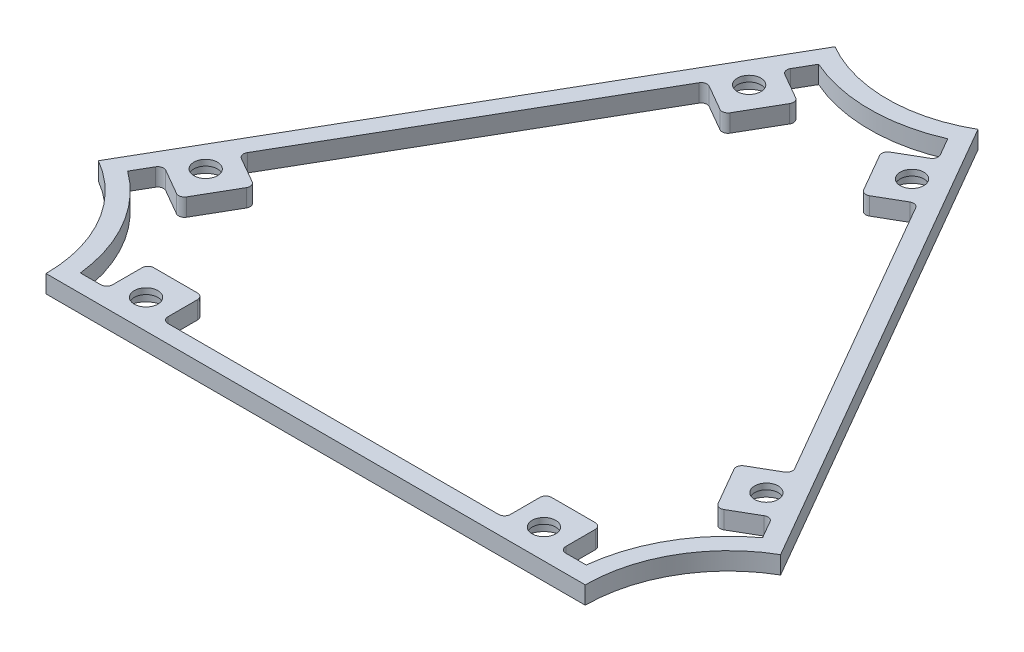
SolidWorks part; units mm, degrees
ref_plane "Front Plane" through (0, 0, 0) normal (0, 0, 1) x (1, 0, 0)
ref_plane "Top Plane" through (0, 0, 0) normal (0, 1, 0) x (1, 0, 0)
ref_plane "Right Plane" through (0, 0, 0) normal (1, 0, 0) x (0, 0, -1)
sketch "Sketch2" plane through (0, 0, 0) normal (0, 1, 0) x (1, 0, 0)
  line L0 (-46.9523, -6.4506) -> (-41.8901, -9.3732) construction
  line L1 (-41.3901, -10.8166) -> (-45.0901, -17.2252) construction
  line L2 (-46.5901, -17.5139) -> (-51.6523, -14.5912) construction
  line L3 (-51.6523, -14.5912) -> (-55.3023, -20.9132) construction
  line L4 (11.8276, 40.3871) -> (11.3276, 41.2532)
  line L5 (-57.9003, -19.4132) -> (-45.9003, 1.3714) construction
  line L6 (29.0625, -30.4366) -> (38.4625, -30.4366)
  line L7 (-43.3023, -0.1286) -> (-46.9523, -6.4506) construction
  line L8 (-38.4625, -37.4366) -> (-38.4625, -31.5913) construction
  line L9 (-37.4625, -30.4366) -> (-30.0625, -30.4366) construction
  line L10 (-29.0625, -31.5913) -> (-29.0625, -37.4366) construction
  line L11 (-29.0625, -37.4366) -> (-21.7625, -37.4366) construction
  line L12 (-40.8901, -9.9506) -> (-45.5901, -18.0912)
  line L13 (-21.7625, -40.4366) -> (-45.7625, -40.4366) construction
  line L14 (49.0148, -28.2987) -> (46.4168, -26.7987) construction
  line L15 (-45.7625, -37.4366) -> (-38.4625, -37.4366) construction
  line L16 (29.0625, -37.4366) -> (29.0625, -31.5913) construction
  line L17 (30.0625, -30.4366) -> (37.4625, -30.4366) construction
  line L18 (38.4625, -31.5913) -> (38.4625, -37.4366) construction
  line L19 (38.4625, -37.4366) -> (45.7625, -37.4366) construction
  line L20 (0, 53.5974) -> (0, 56.5974) construction
  line L21 (45.7625, -40.4366) -> (21.7625, -40.4366) construction
  line L22 (-46.4168, -26.7987) -> (-49.0148, -28.2987) construction
  line L23 (21.7625, -37.4366) -> (29.0625, -37.4366) construction
  line L24 (51.6523, -14.5912) -> (46.5901, -17.5139) construction
  line L25 (45.0901, -17.2252) -> (41.3901, -10.8166) construction
  line L26 (41.8901, -9.3732) -> (46.9523, -6.4506) construction
  line L27 (46.9523, -6.4506) -> (43.3023, -0.1286) construction
  line L29 (45.9003, 1.3714) -> (57.9003, -19.4132) construction
  line L31 (55.3023, -20.9132) -> (51.6523, -14.5912) construction
  line L32 (11.3276, 41.2532) -> (7.6276, 47.6618) construction
  line L33 (8.1276, 49.1051) -> (13.1898, 52.0278) construction
  line L34 (13.1898, 52.0278) -> (9.5398, 58.3498) construction
  line L36 (12.1378, 59.8498) -> (24.1378, 39.0652) construction
  line L38 (21.5398, 37.5652) -> (17.8898, 43.8871) construction
  line L39 (17.8898, 43.8871) -> (12.8276, 40.9645) construction
  line L40 (-13.1898, 52.0278) -> (-8.1276, 49.1051) construction
  line L41 (-7.6276, 47.6618) -> (-11.3276, 41.2532) construction
  line L42 (-12.8276, 40.9645) -> (-17.8898, 43.8871) construction
  line L43 (-17.8898, 43.8871) -> (-21.5398, 37.5652) construction
  line L45 (-24.1378, 39.0652) -> (-12.1378, 59.8498) construction
  line L47 (-9.5398, 58.3498) -> (-13.1898, 52.0278) construction
  line L48 (-46.9523, -6.4506) -> (-40.8901, -9.9506)
  line L49 (-11.3276, 41.2532) -> (-11.8276, 40.3871)
  line L50 (-45.5901, -18.0912) -> (-51.6523, -14.5912)
  line L51 (-51.6523, -14.5912) -> (-53.885, -18.4584)
  line L52 (43.3023, -0.1286) -> (45.9003, 1.3714) construction
  line L53 (-57.9003, -19.4132) -> (-45.9003, 1.3714)
  line L55 (-43.3023, -0.1286) -> (-46.9523, -6.4506)
  line L56 (-38.4625, -37.4366) -> (-38.4625, -30.4366)
  line L57 (-38.4625, -30.4366) -> (-30.0625, -30.4366)
  line L58 (-29.0625, -30.4366) -> (-29.0625, -37.4366)
  line L59 (-29.0625, -37.4366) -> (-21.7625, -37.4366)
  line L61 (-21.7625, -40.4366) -> (-45.7625, -40.4366)
  line L63 (-42.928, -37.4366) -> (-38.4625, -37.4366)
  line L64 (29.0625, -37.4366) -> (29.0625, -30.4366)
  line L65 (-30.0625, -30.4366) -> (-29.0625, -30.4366)
  line L66 (38.4625, -30.4366) -> (38.4625, -37.4366)
  line L67 (38.4625, -37.4366) -> (42.928, -37.4366)
  line L69 (45.7625, -40.4366) -> (21.7625, -40.4366)
  line L71 (21.7625, -37.4366) -> (29.0625, -37.4366)
  line L72 (51.6523, -14.5912) -> (45.5901, -18.0912)
  line L73 (45.5901, -18.0912) -> (40.8901, -9.9506)
  line L74 (40.8901, -9.9506) -> (46.9523, -6.4506)
  line L75 (46.9523, -6.4506) -> (43.3023, -0.1286)
  line L77 (45.9003, 1.3714) -> (57.9003, -19.4132)
  line L79 (53.885, -18.4584) -> (51.6523, -14.5912)
  line L80 (11.3276, 41.2532) -> (7.1276, 48.5278)
  line L81 (7.1276, 48.5278) -> (13.1898, 52.0278)
  line L82 (13.1898, 52.0278) -> (10.957, 55.895)
  line L84 (12.1378, 59.8498) -> (24.1378, 39.0652)
  line L86 (21.5398, 37.5652) -> (17.8898, 43.8871)
  line L87 (17.8898, 43.8871) -> (11.8276, 40.3871)
  line L88 (-13.1898, 52.0278) -> (-7.1276, 48.5278)
  line L89 (-7.1276, 48.5278) -> (-11.3276, 41.2532)
  line L90 (-11.8276, 40.3871) -> (-17.8898, 43.8871)
  line L91 (-17.8898, 43.8871) -> (-21.5398, 37.5652)
  line L93 (-24.1378, 39.0652) -> (-12.1378, 59.8498)
  line L95 (-10.957, 55.895) -> (-13.1898, 52.0278)
  line L98 (-45.9003, 1.3714) -> (-24.1378, 39.0652)
  line L99 (-43.3023, -0.1286) -> (-21.5398, 37.5652)
  line L100 (24.1378, 39.0652) -> (45.9003, 1.3714)
  line L101 (43.3023, -0.1286) -> (21.5398, 37.5652)
  line L102 (21.7625, -40.4366) -> (-21.7625, -40.4366)
  line L103 (-21.7625, -37.4366) -> (21.7625, -37.4366)
  arc A0 (57.9003, -19.4132) -> (45.7625, -40.4366) centre (70.0382, -40.4366) ccw
  arc A1 (53.885, -18.4584) -> (42.928, -37.4366) centre (70.0382, -40.4366) ccw
  arc A2 (12.1378, 59.8498) -> (-12.1378, 59.8498) centre (0, 80.8731) cw
  arc A3 (10.957, 55.895) -> (-10.957, 55.895) centre (0, 80.8731) cw
  arc A4 (-42.928, -37.4366) -> (-53.885, -18.4584) centre (-70.0382, -40.4366) ccw
  arc A5 (-45.7625, -40.4366) -> (-57.9003, -19.4132) centre (-70.0382, -40.4366) ccw
extrude "Boss-Extrude2" add sketch "Sketch2" along normal blind 3
sketch "Sketch3" plane through (0, 3, 0) normal (0, 1, 0) x (1, 0, 0)
  circle A0 centre (33.7625, -35.4526) radius 2 construction
  circle A1 centre (33.7625, -35.4526) radius 2
  circle A2 centre (-33.7625, -35.4526) radius 2 construction
  circle A3 centre (-47.5841, -11.5129) radius 2 construction
  circle A4 centre (47.5841, -11.5129) radius 2 construction
  circle A5 centre (13.8216, 46.9655) radius 2 construction
  circle A6 centre (-13.8216, 46.9655) radius 2 construction
  circle A7 centre (-33.7625, -35.4526) radius 2
  circle A8 centre (-47.5841, -11.5129) radius 2
  circle A9 centre (47.5841, -11.5129) radius 2
  circle A10 centre (13.8216, 46.9655) radius 2
  circle A11 centre (-13.8216, 46.9655) radius 2
extrude "Cut-Extrude1" cut sketch "Sketch3" against normal through all
sketch "Sketch4" plane through (0, 0, 0) normal (0, -1, 0) x (1, 0, 0)
  line L0 (46.3762, 16.0208) -> (52.092, 12.7208)
  line L1 (-37.0625, 32.1526) -> (-30.4625, 32.1526)
  line L2 (-37.0625, 32.1526) -> (-37.0625, 38.7526)
  line L3 (-37.0625, 38.7526) -> (-30.4625, 38.7526)
  line L4 (-30.4625, 32.1526) -> (-30.4625, 38.7526)
  line L5 (-37.0625, 32.1526) -> (-30.4625, 38.7526) construction
  line L6 (-37.0625, 38.7526) -> (-30.4625, 32.1526) construction
  line L7 (37.0625, 32.1526) -> (30.4625, 32.1526)
  line L8 (37.0625, 32.1526) -> (37.0625, 38.7526)
  line L9 (37.0625, 38.7526) -> (30.4625, 38.7526)
  line L10 (30.4625, 32.1526) -> (30.4625, 38.7526)
  line L11 (37.0625, 32.1526) -> (30.4625, 38.7526) construction
  line L12 (37.0625, 38.7526) -> (30.4625, 32.1526) construction
  line L13 (46.3762, 16.0208) -> (43.0762, 10.305)
  line L14 (43.0762, 10.305) -> (48.792, 7.005)
  line L15 (52.092, 12.7208) -> (48.792, 7.005)
  line L16 (12.6137, -42.4576) -> (18.3295, -45.7576)
  line L17 (9.3137, -48.1734) -> (12.6137, -42.4576)
  line L18 (9.3137, -48.1734) -> (15.0295, -51.4734)
  line L19 (15.0295, -51.4734) -> (18.3295, -45.7576)
  line L20 (-9.3137, -48.1734) -> (-15.0295, -51.4734)
  line L21 (-9.3137, -48.1734) -> (-12.6137, -42.4576)
  line L22 (-12.6137, -42.4576) -> (-18.3295, -45.7576)
  line L23 (-15.0295, -51.4734) -> (-18.3295, -45.7576)
  line L24 (-43.0762, 10.305) -> (-48.792, 7.005)
  line L25 (-46.3762, 16.0208) -> (-43.0762, 10.305)
  line L26 (-46.3762, 16.0208) -> (-52.092, 12.7208)
  line L27 (-52.092, 12.7208) -> (-48.792, 7.005)
  point P0 (-33.7625, 35.4526)
  point P6 (33.7625, 35.4526)
  point P30 (0, 0)
  dimension "D1" = 6.6
  dimension "D2" = 3
extrude "Cut-Extrude2" [suppressed] cut sketch "Sketch4" against normal blind 2
fillet "Fillet2" radius 1 24 edges at (-40.8901, 1.5, 9.9506) (-45.5901, 1.5, 18.0912) (-51.6523, 1.5, 14.5912) (-38.4625, 1.5, 37.4366) (-38.4625, 1.5, 30.4366) (-29.0625, 1.5, 30.4366) (-29.0625, 1.5, 37.4366) (29.0625, 1.5, 37.4366) (29.0625, 1.5, 30.4366) (38.4625, 1.5, 30.4366) (38.4625, 1.5, 37.4366) (45.5901, 1.5, 18.0912) (40.8901, 1.5, 9.9506) (46.9523, 1.5, 6.4506) (17.8898, 1.5, -43.8871) (11.8276, 1.5, -40.3871) (7.1276, 1.5, -48.5278) (13.1898, 1.5, -52.0278) (-13.1898, 1.5, -52.0278) (-7.1276, 1.5, -48.5278) (-11.8276, 1.5, -40.3871) (-17.8898, 1.5, -43.8871) (-46.9523, 1.5, 6.4506) (51.6523, 1.5, 14.5912)
sketch "Sketch5" plane through (0, 0, 0) normal (0, -1, 0) x (1, 0, 0)
  circle A0 centre (47.5841, 11.5129) radius 3.3
  circle A1 centre (33.7625, 35.4526) radius 3.3
  circle A2 centre (-13.8216, -46.9655) radius 3.3
  circle A3 centre (13.8216, -46.9655) radius 3.3
  circle A4 centre (-33.7625, 35.4526) radius 3.3
  circle A5 centre (-47.5841, 11.5129) radius 3.3
  point P20 (0, 0)
  dimension "D1" = 6.6
  dimension "D2" = 3
extrude "Cut-Extrude3" cut sketch "Sketch5" against normal offset from surface (2 mm away) 1 up to face at (-13.8216, 3, -44.9655)
